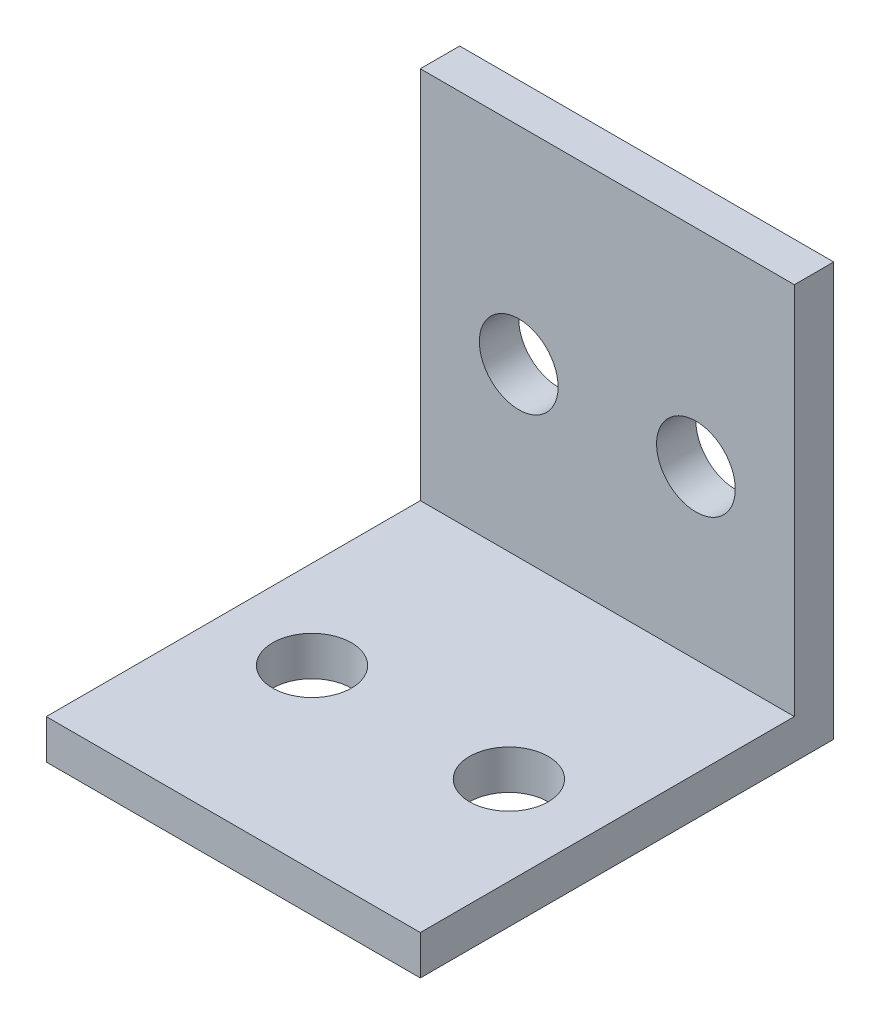
SolidWorks part; units mm, degrees
material "1060 Alloy"
ref_plane "Front Plane" through (0, 0, 0) normal (0, 0, 1) x (1, 0, 0)
ref_plane "Top Plane" through (0, 0, 0) normal (0, 1, 0) x (1, 0, 0)
ref_plane "Right Plane" through (0, 0, 0) normal (1, 0, 0) x (0, 0, -1)
sketch "Sketch1" plane through (0, 0, 0) normal (0, 0, 1) x (1, 0, 0)
  line L1 (-9.5, 10.5) -> (9.5, 10.5)
  line L2 (-9.5, 10.5) -> (-9.5, -10.5)
  line L3 (-9.5, -10.5) -> (9.5, -10.5)
  line L4 (9.5, 10.5) -> (9.5, -10.5)
  line L5 (-9.5, 10.5) -> (9.5, -10.5) construction
  line L6 (-9.5, -10.5) -> (9.5, 10.5) construction
  point P0 (0, 0)
  dimension "D1" = 19
  dimension "D2" = 21
extrude "Boss-Extrude1" add sketch "Sketch1" along normal blind 2
sketch "Sketch3" plane through (0, 0, 2) normal (0, 0, 1) x (1, 0, 0)
  line L0 (-9.5, 10.5) -> (-9.5, -10.5) construction
  line L1 (-9.5, -8.5) -> (9.5, -8.5)
  line L2 (-9.5, -8.5) -> (-9.5, -10.5)
  line L3 (-9.5, -10.5) -> (9.5, -10.5)
  line L4 (9.5, -8.5) -> (9.5, -10.5)
  dimension "D1" = 2
extrude "Boss-Extrude3" add sketch "Sketch3" along normal blind 19
sketch "Sketch6" plane through (0, 0, 2) normal (0, 0, 1) x (1, 0, 0)
  line L0 (-4.5, 10.5) -> (-4.5, -8.5) construction
  line L1 (9.5, 10.5) -> (-9.5, 10.5) construction
  line L2 (9.5, -8.5) -> (-9.5, -8.5) construction
  line L5 (-9.5, 10.5) -> (-9.5, -8.5) construction
  line L7 (-12.3047, 0) -> (11.2054, 0) construction
  line L8 (0, 12.3166) -> (0, -9.4302) construction
  circle A0 centre (-4.5, 0) radius 2
  circle A1 centre (4.5, 0) radius 2
  dimension "D3" = 4
  dimension "D1" = 5
extrude "Cut-Extrude1" cut sketch "Sketch6" against normal blind 2
sketch "Sketch7" plane through (0, -8.5, 0) normal (0, 1, 0) x (1, 0, 0)
  line L0 (-5, -1.3198) -> (-5, -20.5693) construction
  line L1 (-9.5, -12) -> (12.6086, -12) construction
  line L2 (-9.5, -21) -> (-9.5, -2) construction
  line L4 (9.5, 0) -> (-9.5, 0) construction
  line L6 (0, -1.3198) -> (0, -20.2359) construction
  circle A0 centre (-5, -12) radius 2
  circle A1 centre (5, -12) radius 2
  dimension "D4" = 4
  dimension "D1" = 12
  dimension "D2" = 4.5
  dimension "D3" = 5
extrude "Cut-Extrude2" cut sketch "Sketch7" against normal blind 2
